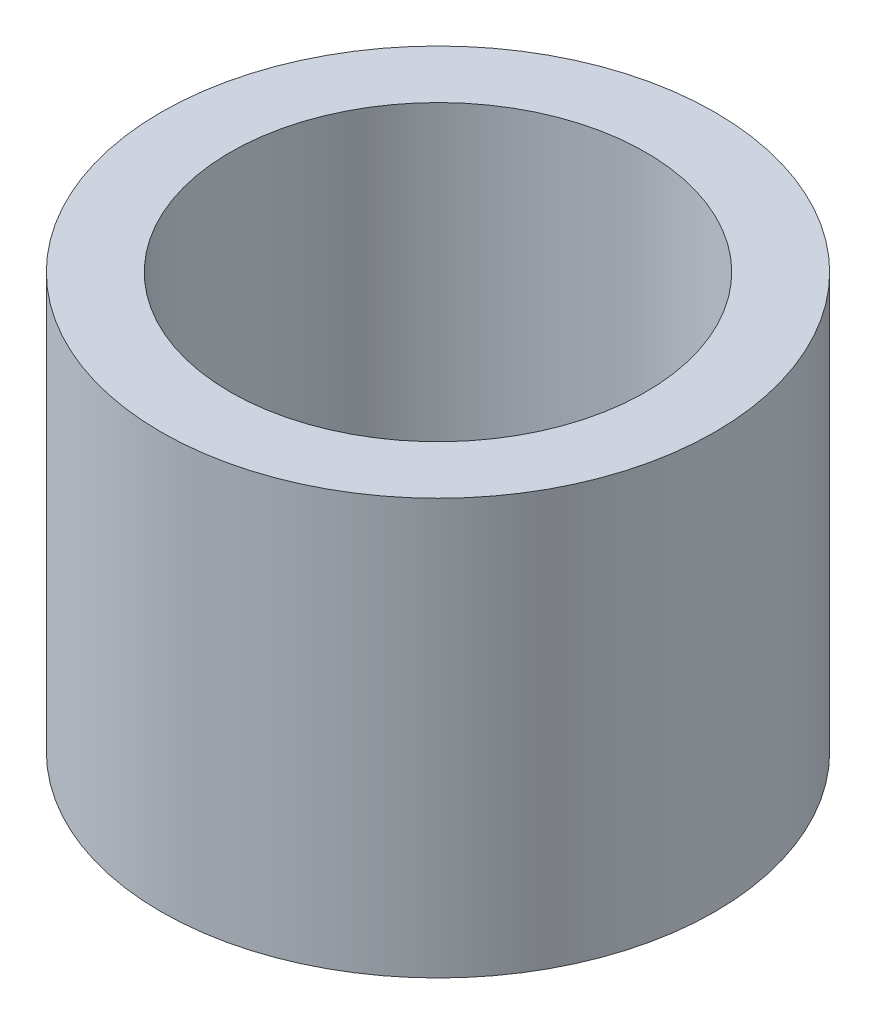
SolidWorks part; units mm, degrees
ref_plane "Front Plane" through (0, 0, 0) normal (0, 0, 1) x (1, 0, 0)
ref_plane "Top Plane" through (0, 0, 0) normal (0, 1, 0) x (1, 0, 0)
ref_plane "Right Plane" through (0, 0, 0) normal (1, 0, 0) x (0, 0, -1)
sketch "Sketch1" plane through (0, 0, 0) normal (0, 1, 0) x (1, 0, 0)
  circle A0 centre (0, 0) radius 7.5
  circle A1 centre (0, 0) radius 10
  dimension "D1" = 20
  dimension "D2" = 15
extrude "Boss-Extrude1" add sketch "Sketch1" along normal blind 15
